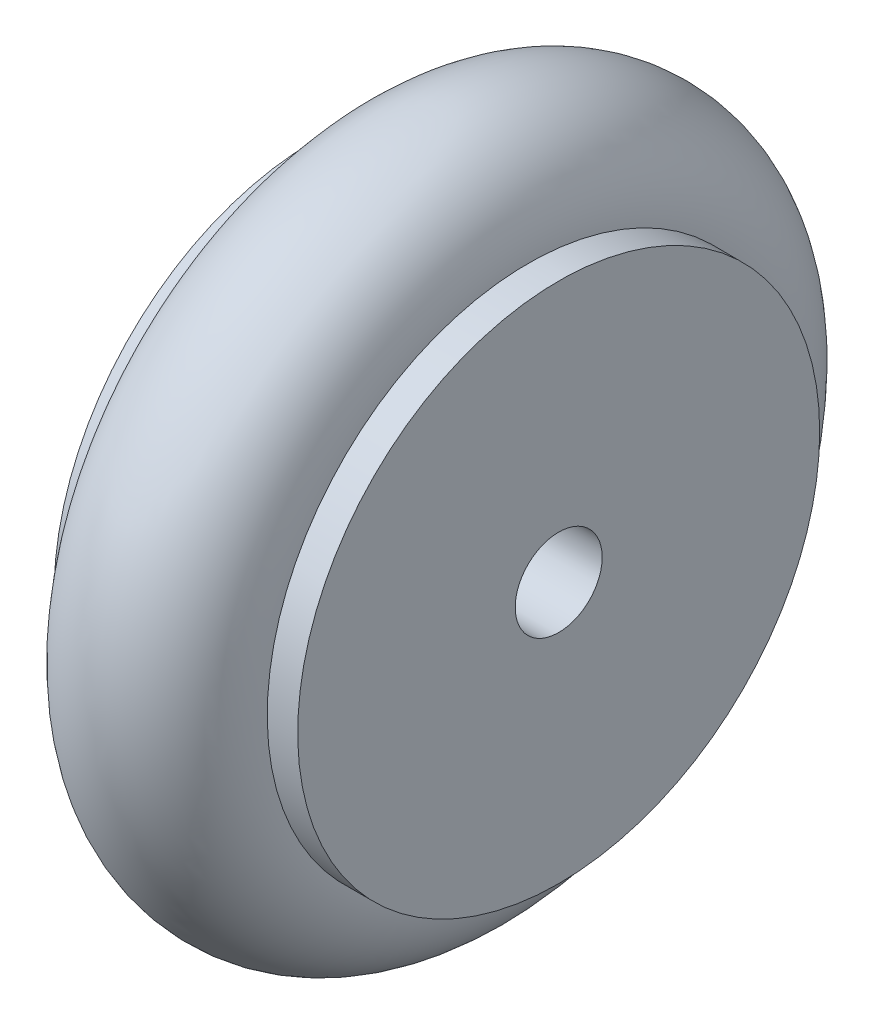
SolidWorks part; units mm, degrees
ref_plane "Front Plane" through (0, 0, 0) normal (0, 0, 1) x (1, 0, 0)
ref_plane "Top Plane" through (0, 0, 0) normal (0, 1, 0) x (1, 0, 0)
ref_plane "Right Plane" through (0, 0, 0) normal (1, 0, 0) x (0, 0, -1)
sketch "Sketch1" plane through (0, 0, 0) normal (1, 0, 0) x (0, 0, -1)
  circle A0 centre (0, 0) radius 3
  dimension "D1" = 6
extrude "Boss-Extrude1" add sketch "Sketch1" along normal blind 2.8
sketch "Sketch4" plane through (0, 0, 0) normal (0, 0, 1) x (1, 0, 0)
  line L0 (2.8, 3) -> (0, 3) construction
  line L1 (0, 0) -> (2.8, 0) construction
  line L2 (0, 3) -> (0, -3) construction
  line L3 (2.8, -3) -> (2.8, 3) construction
  circle A0 centre (1.4, 3) radius 1.05
  dimension "D1" = 2.1
revolve "Revolve1" add sketch "Sketch4" angle 360 about L1
sketch "Sketch5" plane through (2.8, 0, 0) normal (1, 0, 0) x (0, 0, -1)
  circle A0 centre (0, 0) radius 0.5
  dimension "D1" = 1
extrude "Cut-Extrude1" cut sketch "Sketch5" against normal up to surface (2.8 mm away) up to face at (0, 0, -3)
